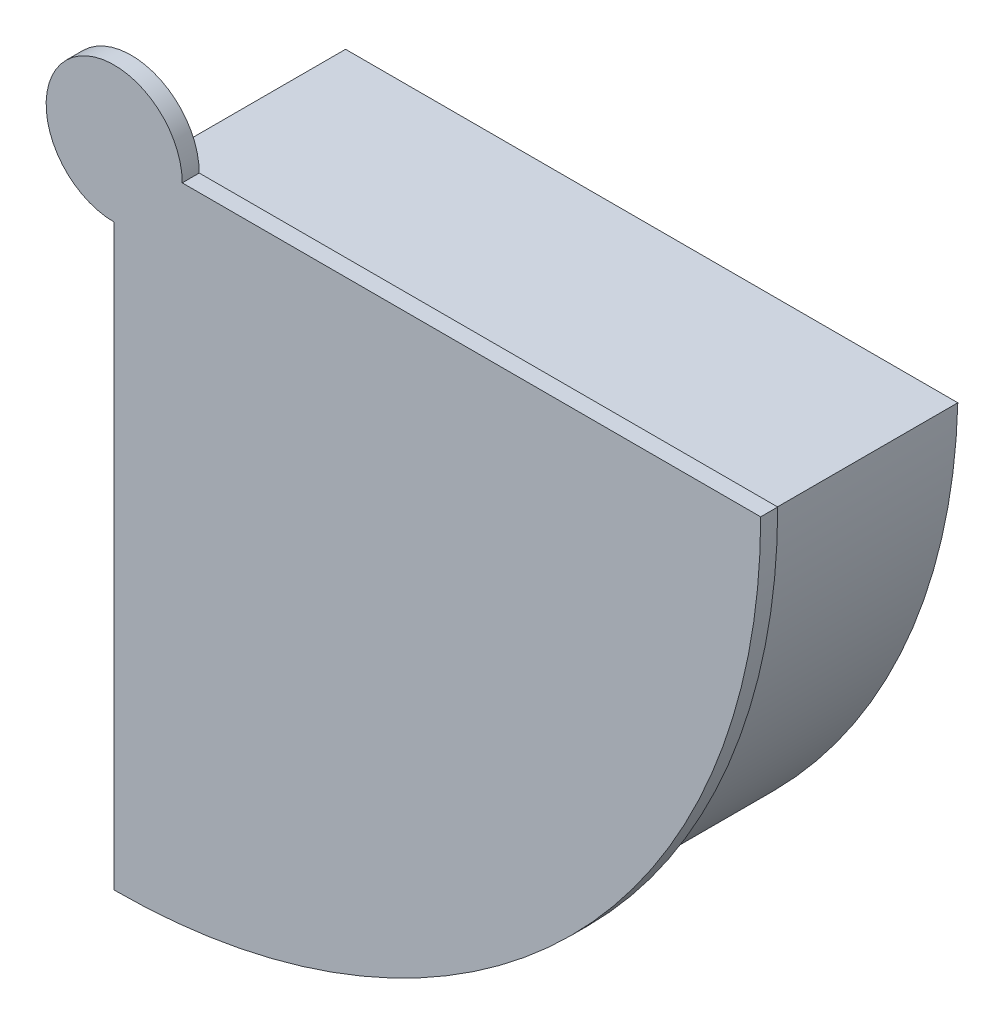
SolidWorks part; units mm, degrees
ref_plane "前视基准面" through (0, 0, 0) normal (0, 0, 1) x (1, 0, 0)
ref_plane "上视基准面" through (0, 0, 0) normal (0, 1, 0) x (1, 0, 0)
ref_plane "右视基准面" through (0, 0, 0) normal (1, 0, 0) x (0, 0, -1)
sketch "草图1" plane through (0, 0, 0) normal (0, 0, 1) x (1, 0, 0)
  line L0 (0, 0) -> (0, -190)
  line L1 (0, 0) -> (190, 0)
  arc A0 (0, -190) -> (190, 0) centre (0, 0) ccw
extrude "凸台-拉伸1" add sketch "草图1" along normal blind 5
sketch "草图2" plane through (0, 0, 0) normal (0, 0, -1) x (-1, 0, 0)
  line L0 (-9.7553, -10.014) -> (-9.7553, -179.7355)
  line L4 (-5, -5) -> (-184.9324, -5)
  line L5 (-5, -184.9324) -> (-5, -5)
  line L6 (-5, -5) -> (-184.9324, -5)
  line L7 (-5, -184.9324) -> (-5, -5)
  line L8 (-9.7553, -10.014) -> (-179.7212, -10.014)
  arc A1 (-179.7212, -10.014) -> (-9.7553, -179.7355) centre (0, 0) ccw
  arc A2 (-184.9324, -5) -> (-5, -184.9324) centre (0, 0) ccw
  arc A3 (-184.9324, -5) -> (-5, -184.9324) centre (0, 0) ccw
  dimension "D1" = 5
extrude "凸台-拉伸2" add sketch "草图2" along normal blind 58
sketch "草图3" plane through (0, 0, 5) normal (0, 0, 1) x (1, 0, 0)
  circle A0 centre (0, 0) radius 20
extrude "凸台-拉伸3" add sketch "草图3" against normal blind 5
